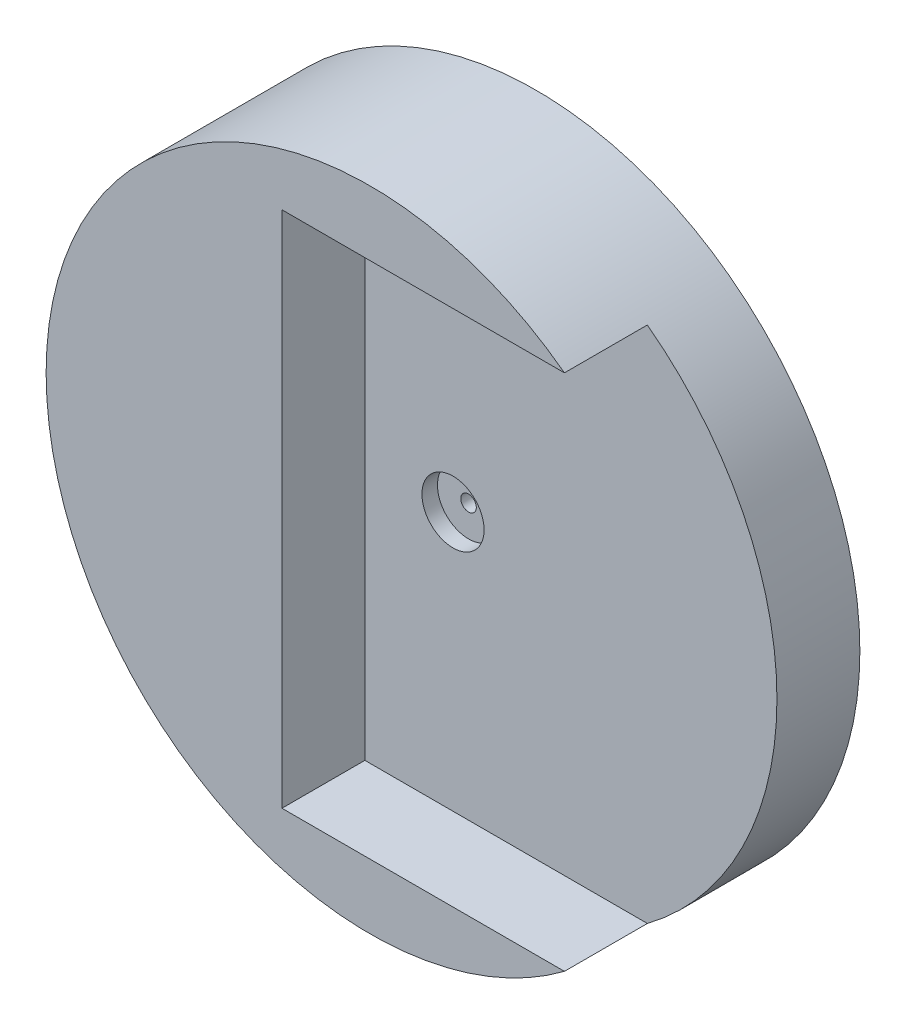
SolidWorks part; units mm, degrees
material "Perspex (TM) GS Acrylic Cast Sheet"
ref_plane "Front Plane" through (0, 0, 0) normal (0, 0, 1) x (1, 0, 0)
ref_plane "Top Plane" through (0, 0, 0) normal (0, 1, 0) x (1, 0, 0)
ref_plane "Right Plane" through (0, 0, 0) normal (1, 0, 0) x (0, 0, -1)
sketch "Sketch1" plane through (0, 0, 0) normal (0, 0, 1) x (1, 0, 0)
  circle A0 centre (0, 0) radius 57.5
  circle A1 centre (0, 0) radius 62.5
  dimension "D1" = 115
  dimension "D2" = 125
extrude "Boss-Extrude1" add sketch "Sketch1" along normal blind 10
sketch "Sketch2" plane through (0, 0, 10) normal (0, 0, 1) x (1, 0, 0)
  circle A0 centre (0, 0) radius 62.5
  circle A1 centre (0, 0) radius 62.5 construction
extrude "Boss-Extrude2" add sketch "Sketch2" along normal blind 22
sketch "Sketch3" plane through (0, 0, 10) normal (0, 0, -1) x (-1, 0, 0)
  circle A0 centre (0, 0) radius 1.5
  dimension "D1" = 3
extrude "Cut-Extrude1" cut sketch "Sketch3" against normal through all
sketch "Sketch4" plane through (0, 0, 32) normal (0, 0, 1) x (1, 0, 0)
  line L1 (-17, 50) -> (83, 50)
  line L2 (-17, 50) -> (-17, -50)
  line L3 (-17, -50) -> (83, -50)
  line L4 (83, 50) -> (83, -50)
  circle A0 centre (0, 0) radius 1.5 construction
  dimension "D1" = 50
  dimension "D2" = 100
  dimension "D3" = 17
extrude "Cut-Extrude2" cut sketch "Sketch4" against normal blind 16
sketch "Sketch6" plane through (0, 0, 16) normal (0, 0, 1) x (1, 0, 0)
  circle A0 centre (0, 0) radius 6
  dimension "D1" = 12
extrude "Cut-Extrude3" cut sketch "Sketch6" against normal blind 3
